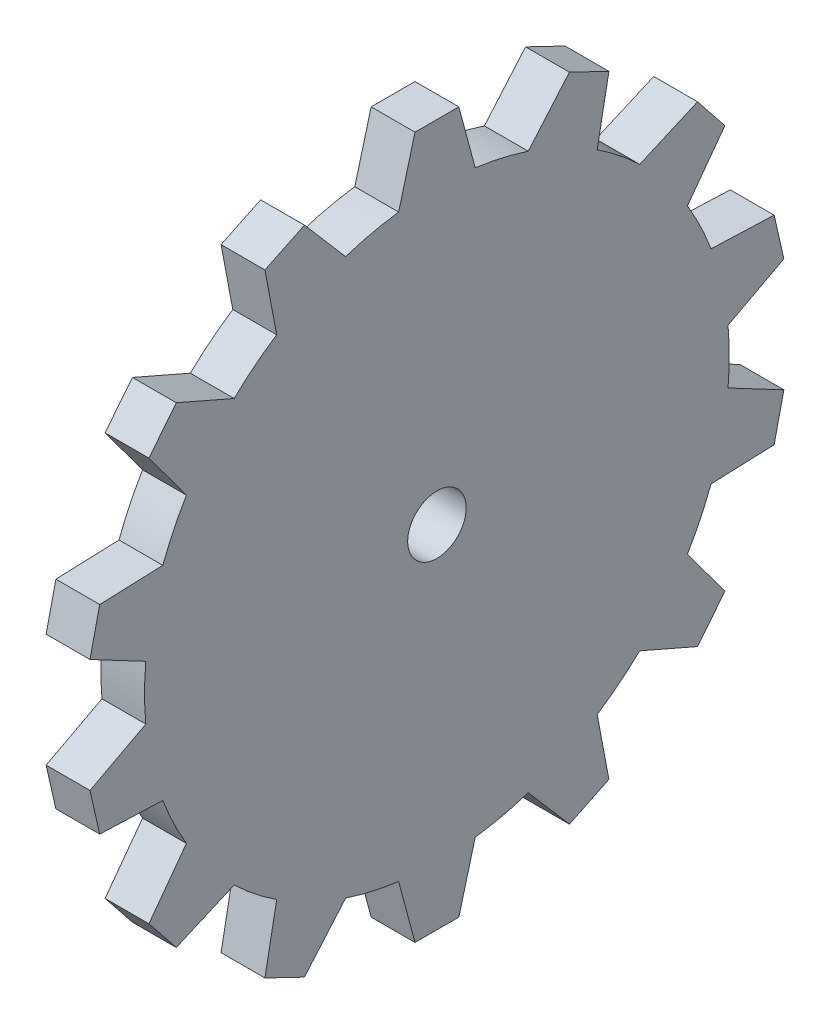
SolidWorks part; units mm, degrees
ref_plane "Front Plane" through (0, 0, 0) normal (0, 0, 1) x (1, 0, 0)
ref_plane "Top Plane" through (0, 0, 0) normal (0, 1, 0) x (1, 0, 0)
ref_plane "Right Plane" through (0, 0, 0) normal (1, 0, 0) x (0, 0, -1)
sketch "Sketch3" plane through (0, 0, 0) normal (1, 0, 0) x (0, 0, -1)
  circle A0 centre (0, 0) radius 20
extrude "Boss-Extrude2" add sketch "Sketch3" along normal blind 3
sketch "Sketch4" plane through (3, 0, 0) normal (1, 0, 0) x (0, 0, -1)
  line L0 (0, 0) -> (0, 25) construction
  line L1 (1.5, 24.0003) -> (2.618, 19.8279)
  line L2 (2.618, 19.8279) -> (-2.618, 19.8279)
  line L3 (-2.618, 19.8279) -> (-1.5, 24.0003)
  line L4 (-1.5, 24.0003) -> (1.5, 24.0003)
  circle A1 centre (0, 0) radius 20 construction
  dimension "D1" = 25
  dimension "D2" = 5.236
  dimension "D3" = 105
  dimension "D4" = 105
  dimension "D5" = 3
extrude "Boss-Extrude3" add sketch "Sketch4" against normal blind 3
pattern_circular "CirPattern1" count 14 over 360 about axis through (0, 0, 0) along (1, 0, 0) of "Boss-Extrude3"
hole_wizard "Ø4.0mm Dowel Hole1" positions "Sketch5" profile "Sketch6" hole size "Ø4.0" standard "ANSI Metric"
sketch "Sketch5" plane through (3, 0, 0) normal (1, 0, 0) x (0, 0, -1)
  point P0 (0, 0)
sketch "Sketch6" plane through (3, 0, 0) normal (0, 1, 0) x (0, 0, -1)
  line L0 (0, 0) -> (0, 4.2017)
  line L1 (0, 4.2017) -> (2, 3)
  line L2 (2, 3) -> (2, 0)
  line L5 (2, 0) -> (0, 0)
  line L10 (0, 4.2017) -> (-2, 3) construction
  line L11 (0, -6.35) -> (0, 107.95) construction
  dimension "Hole Dia." = 4
  dimension "Hole Depth" = 3
  dimension "Drill Angle" = 118
